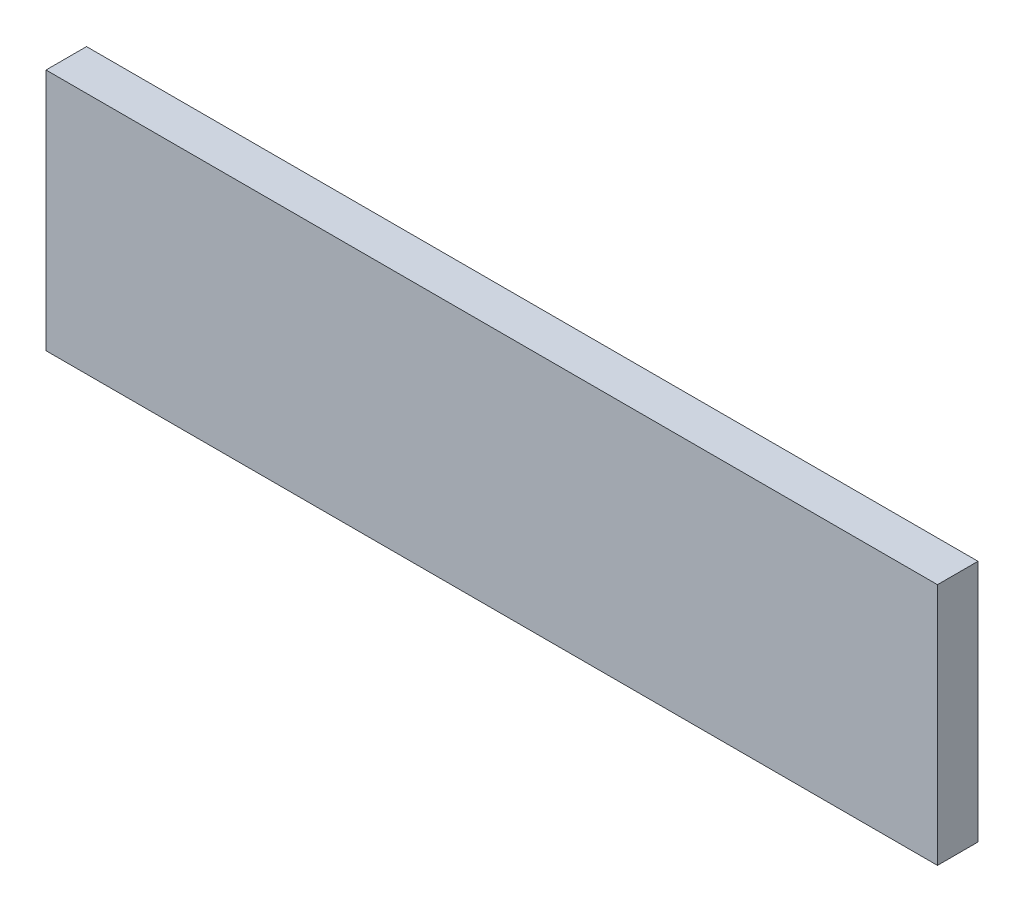
SolidWorks part; units mm, degrees
ref_plane "Front Plane" through (0, 0, 0) normal (0, 0, 1) x (1, 0, 0)
ref_plane "Top Plane" through (0, 0, 0) normal (0, 1, 0) x (1, 0, 0)
ref_plane "Right Plane" through (0, 0, 0) normal (1, 0, 0) x (0, 0, -1)
sketch "Sketch1" plane through (0, 0, 0) normal (1, 0, 0) x (0, 0, -1)
  line L1 (0, 0) -> (50.8, 0)
  line L2 (0, 0) -> (0, 304.8)
  line L3 (0, 304.8) -> (50.8, 304.8)
  line L4 (50.8, 0) -> (50.8, 304.8)
extrude "Boss-Extrude1" add sketch "Sketch1" along normal blind 1117.6
